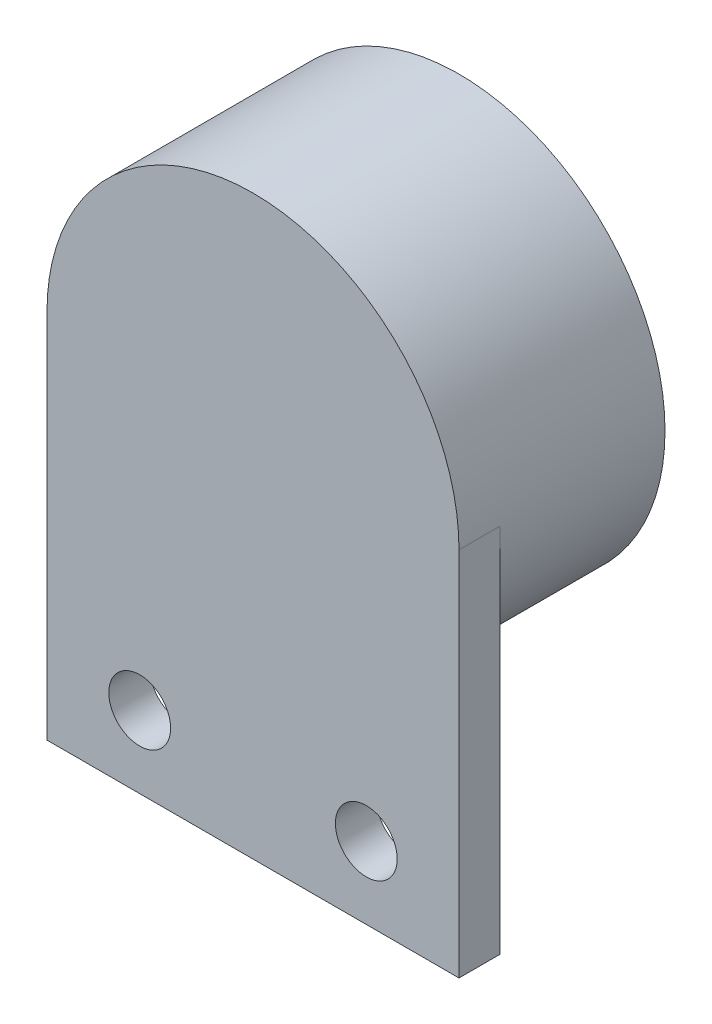
SolidWorks part; units mm, degrees
ref_plane "Front Plane" through (0, 0, 0) normal (0, 0, 1) x (1, 0, 0)
ref_plane "Top Plane" through (0, 0, 0) normal (0, 1, 0) x (1, 0, 0)
ref_plane "Right Plane" through (0, 0, 0) normal (1, 0, 0) x (0, 0, -1)
sketch "Sketch1" plane through (0, 0, 0) normal (0, 0, 1) x (1, 0, 0)
  circle A0 centre (0, 0) radius 10
extrude "Boss-Extrude1" add sketch "Sketch1" along normal blind 10
sketch "Sketch2" plane through (0, 0, 10) normal (0, 0, 1) x (1, 0, 0)
  line L1 (-10, 0) -> (10, 0)
  line L2 (-10, 0) -> (-10, -18)
  line L3 (-10, -18) -> (10, -18)
  line L4 (10, 0) -> (10, -18)
  circle A0 centre (0, 0) radius 10 construction
extrude "Boss-Extrude2" add sketch "Sketch2" against normal blind 2
sketch "Sketch3" plane through (0, 0, 0) normal (0, 0, -1) x (-1, 0, 0)
  circle A0 centre (0, 0) radius 1
extrude "Boss-Extrude3" add sketch "Sketch3" along normal blind 2
sketch "Sketch5" plane through (0, 0, 8) normal (0, 0, -1) x (-1, 0, 0)
  line L0 (10, -18) -> (-10, -18) construction
  line L1 (-10, -18) -> (-10, 0) construction
  circle A0 centre (-5.5, -14.5) radius 1.5
  circle A1 centre (5.5, -14.5) radius 1.5
  point P4 (0, 0)
  point P5 (0, 0)
  dimension "D1" = 3.5
  dimension "D3" = 11
  dimension "D2" = 4.5
extrude "Cut-Extrude1" cut sketch "Sketch5" against normal blind 2
